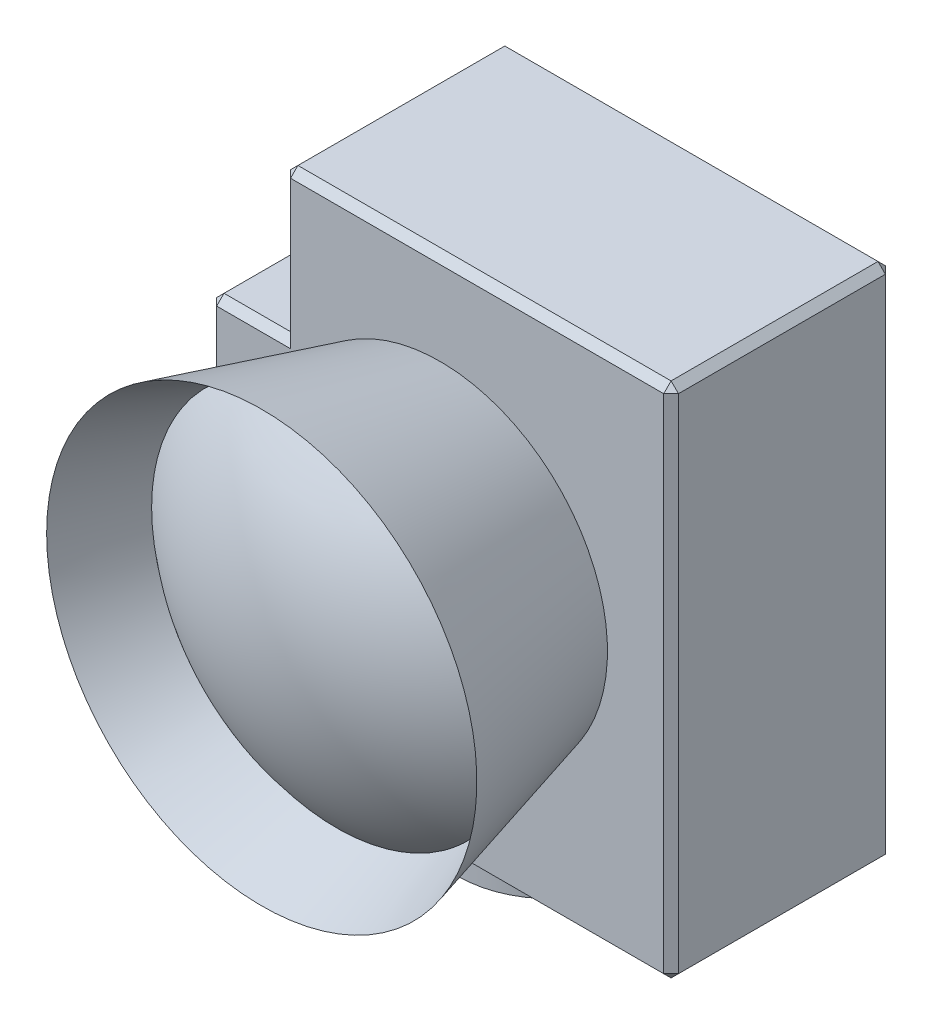
SolidWorks part; units mm, degrees
ref_plane "Front Plane" through (0, 0, 0) normal (0, 0, 1) x (1, 0, 0)
ref_plane "Top Plane" through (0, 0, 0) normal (0, 1, 0) x (1, 0, 0)
ref_plane "Right Plane" through (0, 0, 0) normal (1, 0, 0) x (0, 0, -1)
sketch "Sketch1" plane through (0, 0, 0) normal (0, 0, 1) x (1, 0, 0)
  line L0 (0, 0) -> (0, -18.5305) construction
  line L1 (31.25, 34.982) -> (-21.25, 34.982)
  line L2 (31.25, 34.982) -> (31.25, -35)
  line L3 (31.25, -35) -> (-31.25, -35)
  line L4 (-31.25, 15) -> (-31.25, -35)
  line L5 (-31.25, 15) -> (-21.25, 15)
  line L6 (31.25, -35) -> (-31.25, 35) construction
  line L11 (-21.25, 34.982) -> (-21.25, 15)
  point P0 (0, 0)
  point P2 (0, 0)
  dimension "D1" = 70
  dimension "D2" = 62.5
  dimension "D3" = 21.25
  dimension "D4" = 15
  dimension "D5" = 34.982
extrude "Boss-Extrude1" add sketch "Sketch1" along normal mid plane 30
sketch "Sketch2" plane through (0, -35, 0) normal (0, -1, 0) x (1, 0, 0)
  circle A0 centre (0, 0) radius 12.5
  dimension "D1" = 25
extrude "Boss-Extrude2" add sketch "Sketch2" along normal mid plane 8
chamfer "Chamfer1" distance 1 angle 45 16 edges at (31.25, -35, 0) (5, 34.982, 15) (31.25, -0.009, 15) (0, -35, 15) (-31.25, -10, 15) (5, 34.982, -15) (31.25, -0.009, -15) (0, -35, -15) (-31.25, -10, -15) (-26.25, 15, -15) (-21.25, 24.991, -15) (-21.25, 34.982, 0) (-31.25, 15, 0) (-21.25, 24.991, 15) (-26.25, 15, 15) (31.25, 34.982, 0)
sketch "Sketch4" plane through (0, 0, 0) normal (0, 1, 0) x (1, 0, 0)
  line L0 (-22.6403, -15) -> (-29.1107, -39.1481)
  line L1 (30.25, -15) -> (-20.25, -15) construction
  line L2 (-29.1107, -39.1481) -> (-19.474, -15)
  line L3 (-22.6403, -15) -> (-19.474, -15)
  line L4 (0, 0) -> (0, -50000) construction
  line L5 (0, 0) -> (50000, 0) construction
  dimension "D1" = 75
  dimension "D2" = 25
  dimension "D3" = 26
revolve "Revolve1" add sketch "Sketch4" angle 360 about L4
sketch "Sketch5" plane through (0, 0, 0) normal (0, 1, 0) x (1, 0, 0)
  line L0 (-19.474, -15) -> (-29.1107, -39.1481) construction
  line L1 (0, -33.7502) -> (0, -38.3214)
  arc A0 (-25.0583, -28.9933) -> (0, -38.3214) centre (0, 0) ccw
  spline S0 degree 2 poles (-25.0583, -28.9933) (-12.5291, -33.7502) (0, -33.7502) knots 0 0 0 0.5 0.5 0.5
  dimension "D1" = 38.3214
  dimension "D2" = 33.7502
revolve "Revolve2" add sketch "Sketch5" angle 360 about L4
